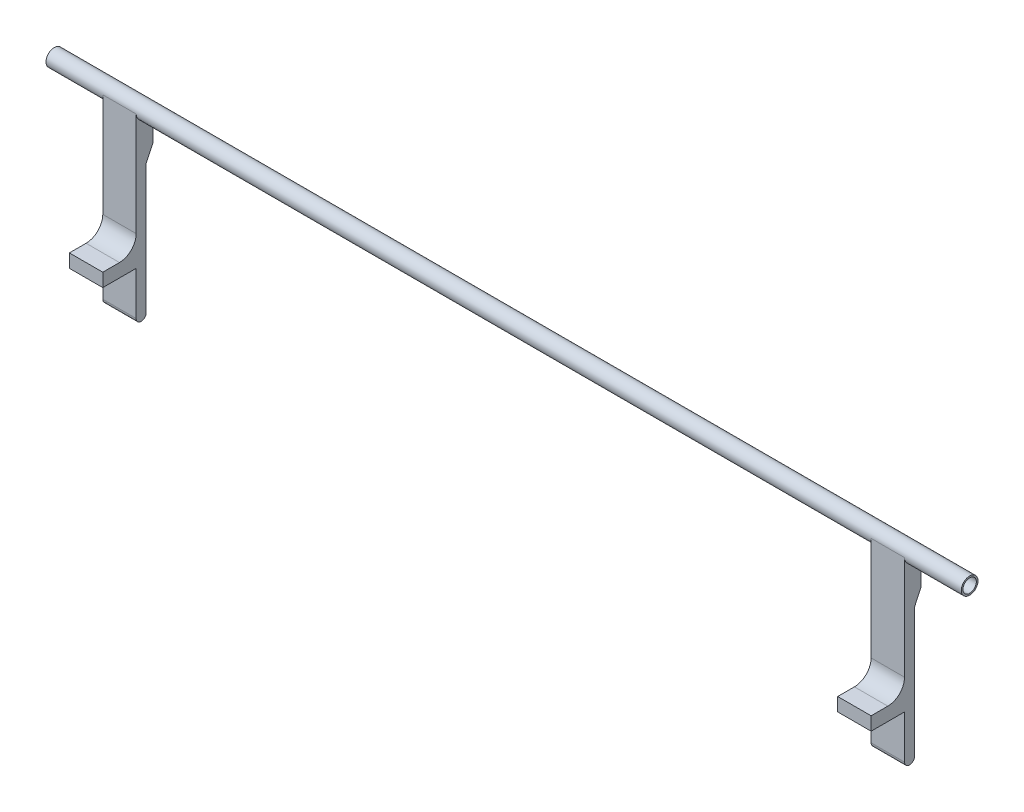
SolidWorks part; units mm, degrees
material "Thornel Mat VMA"
ref_plane "前基準面" through (0, 0, 0) normal (0, 0, 1) x (1, 0, 0)
ref_plane "上基準面" through (0, 0, 0) normal (0, 1, 0) x (1, 0, 0)
ref_plane "右基準面" through (0, 0, 0) normal (1, 0, 0) x (0, 0, -1)
sketch "草圖1" plane through (0, 0, 0) normal (1, 0, 0) x (0, 0, -1)
  circle A0 centre (0, 0) radius 2.5
  circle A1 centre (0, 0) radius 2
  dimension "D1" = 5
  dimension "D2" = 4
extrude "填料-伸長1" add sketch "草圖1" along normal mid plane 274
ref_plane "平面1" through (120, 0, 0) normal (1, 0, 0) x (0, 0, -1)
sketch "草圖3" plane through (120, 0, 0) normal (1, 0, 0) x (0, 0, -1)
  line L0 (2.5, 0) -> (2.5, -10)
  line L2 (-2.5, -53) -> (-2.5, -40)
  line L3 (-2.5, -40) -> (-12.5, -40)
  line L4 (-12.5, -40) -> (-12.5, -36)
  line L5 (-12.5, -36) -> (-7.5, -36)
  line L6 (-2.5, 0) -> (-2.5, -31)
  line L7 (-2.5, -31) -> (-7.5, -31) construction
  line L8 (-7.5, -31) -> (-7.5, -36) construction
  line L9 (2.5, -10) -> (0.5, -14.289)
  line L10 (0.5, -14.289) -> (0.5, -53)
  circle A0 centre (0, 0) radius 2.5 construction
  arc A1 (-2.5, 0) -> (2.5, 0) centre (0, 0) ccw
  arc A2 (-2.5, -31) -> (-7.5, -36) centre (-7.5, -31) cw
  arc A3 (0.5, -53) -> (-2.5, -53) centre (-1, -53) cw
  dimension "D7" = 5
  dimension "D1" = 4
  dimension "D2" = 10
  dimension "D3" = 3
  dimension "D4" = 53
  dimension "D5" = 10
  dimension "D6" = 155
  dimension "D8" = 40
extrude "填料-伸長2" add sketch "草圖3" against normal blind 10
mirror "鏡射1" about plane through (0, 0, 0) normal (1, 0, 0) of "填料-伸長2"
